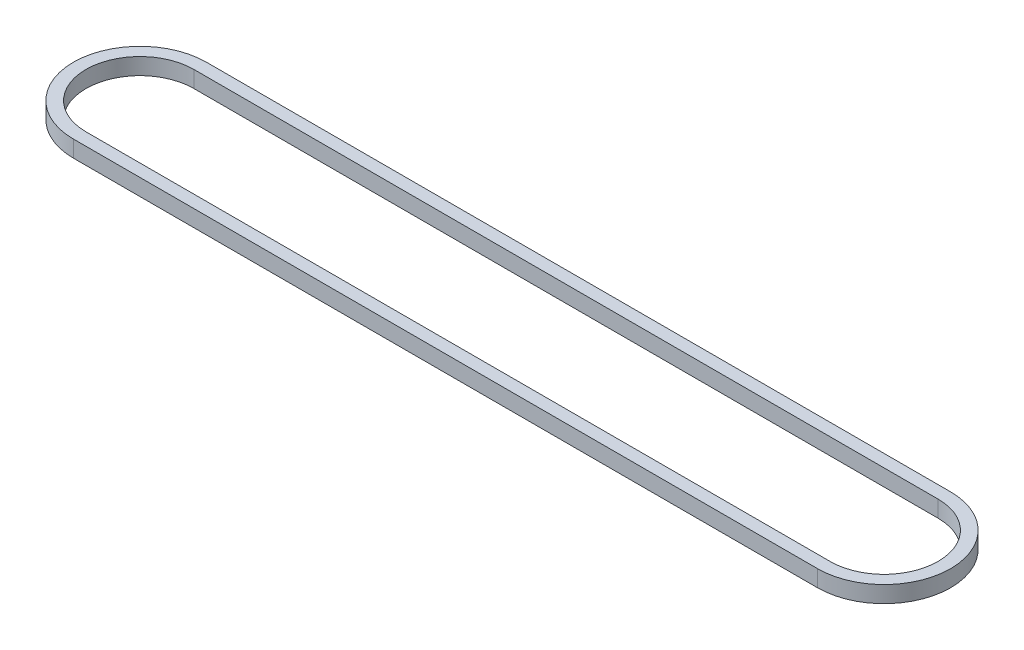
SolidWorks part; units mm, degrees
material "6061 Alloy"
ref_plane "Front Plane" through (0, 0, 0) normal (0, 0, 1) x (1, 0, 0)
ref_plane "Top Plane" through (0, 0, 0) normal (0, 1, 0) x (1, 0, 0)
ref_plane "Right Plane" through (0, 0, 0) normal (1, 0, 0) x (0, 0, -1)
sketch "Sketch1" plane through (0, 0, 0) normal (0, 1, 0) x (1, 0, 0)
  line L0 (-175, 0) -> (175, 0) construction
  line L1 (-175, 0) -> (175, 0) construction
  line L2 (-175, 31.2869) -> (175, 31.287)
  line L3 (-175, -31.2869) -> (175, -31.2869)
  line L4 (-175, 0) -> (175, 0) construction
  line L5 (-175, 25.3942) -> (175, 25.3942)
  line L6 (-175, -25.3942) -> (175, -25.3941)
  line L7 (-175, 25.3942) -> (-175, 31.2869) construction
  arc A0 (-175, 31.2869) -> (-175, -31.2869) centre (-175, 0) ccw
  arc A1 (175, -31.2869) -> (175, 31.287) centre (175, 0) ccw
  arc A2 (-175, 25.3942) -> (-175, -25.3942) centre (-175, 0) ccw
  arc A3 (175, -25.3941) -> (175, 25.3942) centre (175, 0) ccw
  point P0 (0, 0)
  point P4 (0, 0)
  point P10 (0, 0)
  point P18 (-175, 28.3406)
  dimension "D2" = 28.3406
  dimension "D3" = 5.8928
  dimension "D1" = 350
extrude "Boss-Extrude1" add sketch "Sketch1" along normal blind 7.7978 contours L3 A1 L2 A0 | L6 A2 L5 A3
